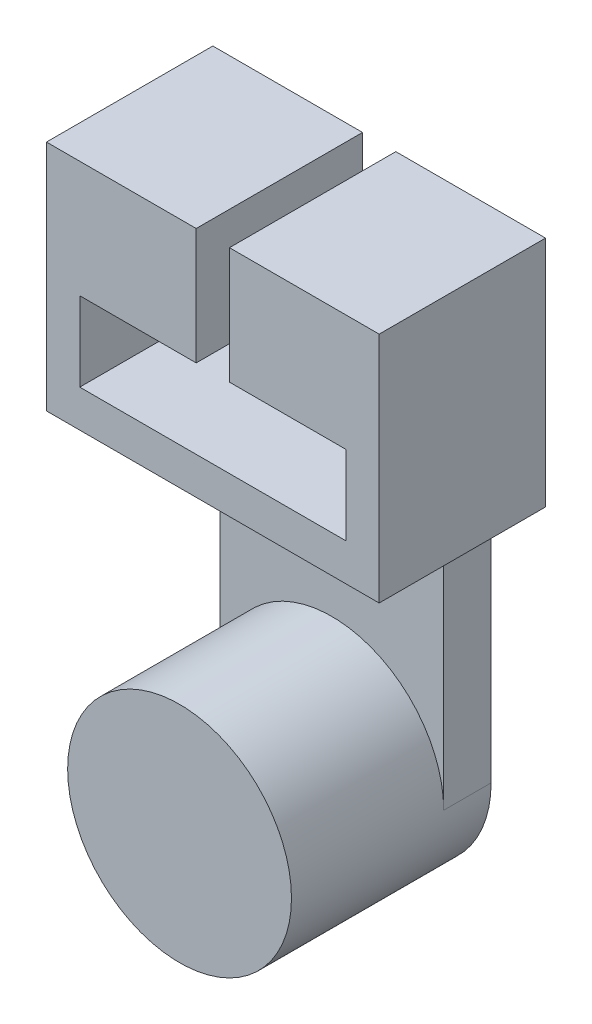
SolidWorks part; units mm, degrees
ref_plane "Front Plane" through (0, 0, 0) normal (0, 0, 1) x (1, 0, 0)
ref_plane "Top Plane" through (0, 0, 0) normal (0, 1, 0) x (1, 0, 0)
ref_plane "Right Plane" through (0, 0, 0) normal (1, 0, 0) x (0, 0, -1)
sketch "Sketch1" plane through (0, 0, 0) normal (0, 0, 1) x (1, 0, 0)
  circle A0 centre (0, 0) radius 10.6807
  dimension "D1" = 21.3614
extrude "Boss-Extrude1" add sketch "Sketch1" along normal blind 19.05
sketch "Sketch2" plane through (0, 0, 0) normal (0, 0, -1) x (-1, 0, 0)
  line L0 (10.6807, 0) -> (-10.6807, 0)
  line L1 (-10.6807, 0) -> (-10.6807, 25.4)
  line L2 (10.6807, 0) -> (10.6807, 25.4)
  line L3 (-10.6807, 25.4) -> (10.6807, 25.4)
  circle A0 centre (0, 0) radius 10.6807 construction
extrude "Boss-Extrude2" add sketch "Sketch2" against normal blind 4.5212
sketch "Sketch3" plane through (0, 25.4, 0) normal (0, 1, 0) x (1, 0, 0)
  line L0 (0, 0) -> (12.7, 0)
  line L1 (0, 0) -> (-12.7, 0)
  line L2 (12.7, 0) -> (12.7, -15.875)
  line L3 (-12.7, 0) -> (-12.7, -15.875)
  line L4 (-12.7, -15.875) -> (12.7, -15.875)
extrude "Boss-Extrude3" add sketch "Sketch3" along normal blind 3.556
sketch "Sketch4" plane through (12.7, 0, 0) normal (1, 0, 0) x (0, 0, -1)
  line L5 (0, 25.4) -> (-15.875, 25.4)
  line L6 (0, 25.4) -> (0, 47.625)
  line L7 (0, 47.625) -> (-15.875, 47.625)
  line L8 (-15.875, 25.4) -> (-15.875, 47.625)
extrude "Boss-Extrude4" add sketch "Sketch4" along normal blind 3.175
sketch "Sketch5" plane through (-12.7, 0, 0) normal (-1, 0, 0) x (0, 0, 1)
  line L1 (15.875, 25.4) -> (0, 25.4)
  line L2 (15.875, 25.4) -> (15.875, 47.625)
  line L3 (15.875, 47.625) -> (0, 47.625)
  line L4 (0, 25.4) -> (0, 47.625)
extrude "Boss-Extrude5" add sketch "Sketch5" along normal blind 3.175
sketch "Sketch7" plane through (-12.7, 0, 0) normal (1, 0, 0) x (0, 0, -1)
  line L0 (-15.875, 47.625) -> (-15.875, 36.5125)
  line L1 (-15.875, 47.625) -> (-15.875, 25.4) construction
  line L2 (-15.875, 36.5125) -> (0, 36.5125)
  line L3 (0, 25.4) -> (0, 47.625) construction
  line L4 (0, 36.5125) -> (0, 47.625)
  line L5 (0, 47.625) -> (-15.875, 47.625)
extrude "Boss-Extrude6" add sketch "Sketch7" along normal blind 11.1125
sketch "Sketch8" plane through (12.7, 0, 0) normal (-1, 0, 0) x (0, 0, 1)
  line L1 (15.875, 36.5125) -> (0, 36.5125)
  line L2 (15.875, 36.5125) -> (15.875, 47.625)
  line L3 (15.875, 47.625) -> (0, 47.625)
  line L4 (0, 36.5125) -> (0, 47.625)
extrude "Boss-Extrude7" add sketch "Sketch8" along normal blind 11.1125
